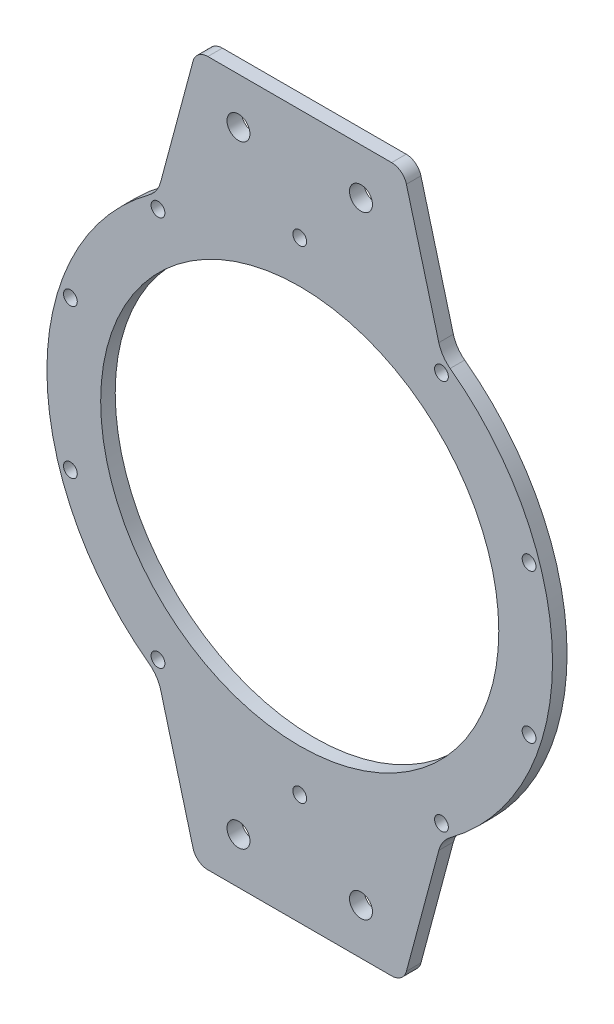
SolidWorks part; units mm, degrees
material "6061-T6 (SS)"
ref_plane "Front Plane" through (0, 0, 0) normal (0, 0, 1) x (1, 0, 0)
ref_plane "Top Plane" through (0, 0, 0) normal (0, 1, 0) x (1, 0, 0)
ref_plane "Right Plane" through (0, 0, 0) normal (1, 0, 0) x (0, 0, -1)
sketch "Sketch1" plane through (0, 0, 0) normal (0, 0, 1) x (1, 0, 0)
  line L0 (-82.55, 0) -> (82.55, 0) construction
  line L1 (0, 0) -> (0, 100) construction
  line L2 (0, 100) -> (-20, 100) construction
  line L3 (-10, 110) -> (10, 110) construction
  line L4 (-10, 110) -> (-10, 90) construction
  line L5 (-10, 90) -> (10, 90) construction
  line L6 (10, 110) -> (10, 90) construction
  line L7 (-10, 110) -> (10, 90) construction
  line L8 (-10, 90) -> (10, 110) construction
  line L9 (0, 100) -> (20, 100) construction
  line L10 (-10, 110) -> (-30, 110) construction
  line L11 (-30, 110) -> (-30, 90) construction
  line L12 (-30, 90) -> (-10, 90) construction
  line L13 (10, 90) -> (30, 90) construction
  line L14 (30, 90) -> (30, 110) construction
  line L15 (30, 110) -> (10, 110) construction
  line L16 (-45.4142, 71.792) -> (-34.8296, 111.2941)
  line L17 (-30, 115) -> (30, 115)
  line L18 (34.8296, 111.2941) -> (45.4142, 71.792)
  line L19 (34.8296, -111.2941) -> (45.4142, -71.792)
  line L20 (-30, -115) -> (30, -115)
  line L21 (-45.4142, -71.792) -> (-34.8296, -111.2941)
  line L22 (-42.5316, 82.55) -> (42.5316, 82.55) construction
  circle A0 centre (0, 0) radius 65
  arc A1 (-49.1228, 66.3435) -> (-49.1228, -66.3435) centre (0, 0) ccw
  circle A2 centre (0, 0) radius 78.74 construction
  circle A13 centre (-20, 100) radius 3.75
  circle A14 centre (20, 100) radius 3.75
  arc A15 (-30, 115) -> (-34.8296, 111.2941) centre (-30, 110) ccw
  arc A16 (34.8296, 111.2941) -> (30, 115) centre (30, 110) ccw
  arc A17 (45.4142, 71.792) -> (49.1228, 66.3435) centre (55.0734, 74.3802) ccw
  arc A18 (-45.4142, 71.792) -> (-49.1228, 66.3435) centre (-55.0734, 74.3802) cw
  arc A19 (49.1228, -66.3435) -> (49.1228, 66.3435) centre (0, 0) ccw
  circle A20 centre (20, -100) radius 3.75
  circle A21 centre (-20, -100) radius 3.75
  arc A22 (45.4142, -71.792) -> (49.1228, -66.3435) centre (55.0734, -74.3802) cw
  arc A23 (34.8296, -111.2941) -> (30, -115) centre (30, -110) cw
  arc A24 (-30, -115) -> (-34.8296, -111.2941) centre (-30, -110) cw
  arc A25 (-45.4142, -71.792) -> (-49.1228, -66.3435) centre (-55.0734, -74.3802) ccw
  circle A26 centre (0, 78.74) radius 2.25
  circle A27 centre (46.2822, 63.702) radius 2.25
  circle A28 centre (74.8862, 24.332) radius 2.25
  circle A29 centre (74.8862, -24.332) radius 2.25
  circle A30 centre (46.2822, -63.702) radius 2.25
  circle A31 centre (0, -78.74) radius 2.25
  circle A32 centre (-46.2822, -63.702) radius 2.25
  circle A33 centre (-74.8862, -24.332) radius 2.25
  circle A34 centre (-74.8862, 24.332) radius 2.25
  circle A35 centre (-46.2822, 63.702) radius 2.25
  arc A36 (-49.1228, 66.3435) -> (49.1228, 66.3435) centre (0, 0) cw construction
  dimension "D1" = 130
  dimension "D2" = 4.5
  dimension "D3" = 157.48
  dimension "D4" = 165.1
  dimension "D7" = 7.5
  dimension "D9" = 5
  dimension "D11" = 10
  dimension "D6" = 20
  dimension "D8" = 90
  dimension "D10" = 15
  dimension "D5" = 10
extrude "Boss-Extrude1" add sketch "Sketch1" along normal mid plane 4.7498
